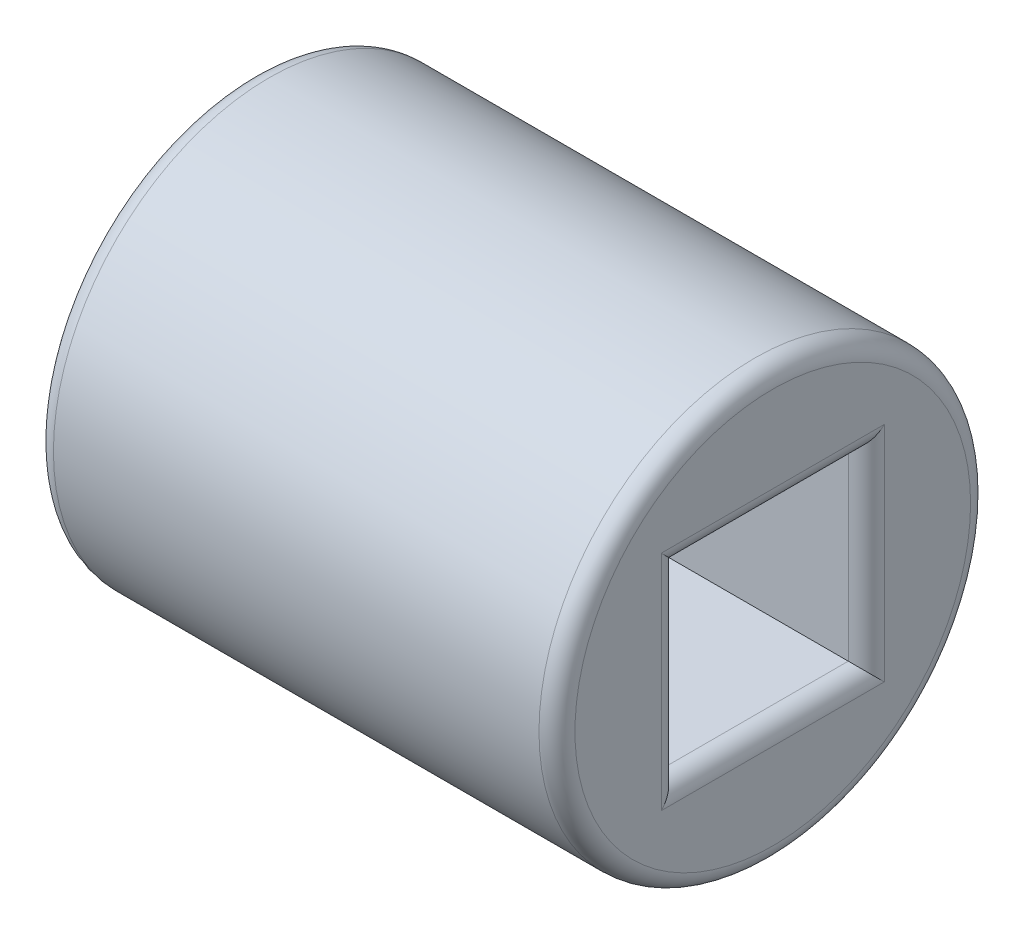
SolidWorks part; units mm, degrees
ref_plane "Front Plane" through (0, 0, 0) normal (0, 0, 1) x (1, 0, 0)
ref_plane "Top Plane" through (0, 0, 0) normal (0, 1, 0) x (1, 0, 0)
ref_plane "Right Plane" through (0, 0, 0) normal (1, 0, 0) x (0, 0, -1)
sketch "Sketch1" plane through (0, 0, 0) normal (1, 0, 0) x (0, 0, -1)
  line L1 (-3.302, 3.302) -> (3.302, 3.302)
  line L2 (-3.302, 3.302) -> (-3.302, -3.302)
  line L3 (-3.302, -3.302) -> (3.302, -3.302)
  line L4 (3.302, 3.302) -> (3.302, -3.302)
  line L5 (-3.302, 3.302) -> (3.302, -3.302) construction
  line L6 (-3.302, -3.302) -> (3.302, 3.302) construction
  circle A0 centre (0, 0) radius 7.62
  dimension "D2" = 15.24
  dimension "D1" = 6.604
extrude "Boss-Extrude1" add sketch "Sketch1" along normal blind 18.415
fillet "Fillet1" radius 0.635 10 edges at (0, -3.302, 0) (0, 0, 3.302) (0, 3.302, 0) (0, 0, -3.302) (0, 0, -7.62) (18.415, 0, 3.302) (18.415, -3.302, 0) (18.415, 0, -3.302) (18.415, 3.302, 0) (18.415, 0, -7.62)
